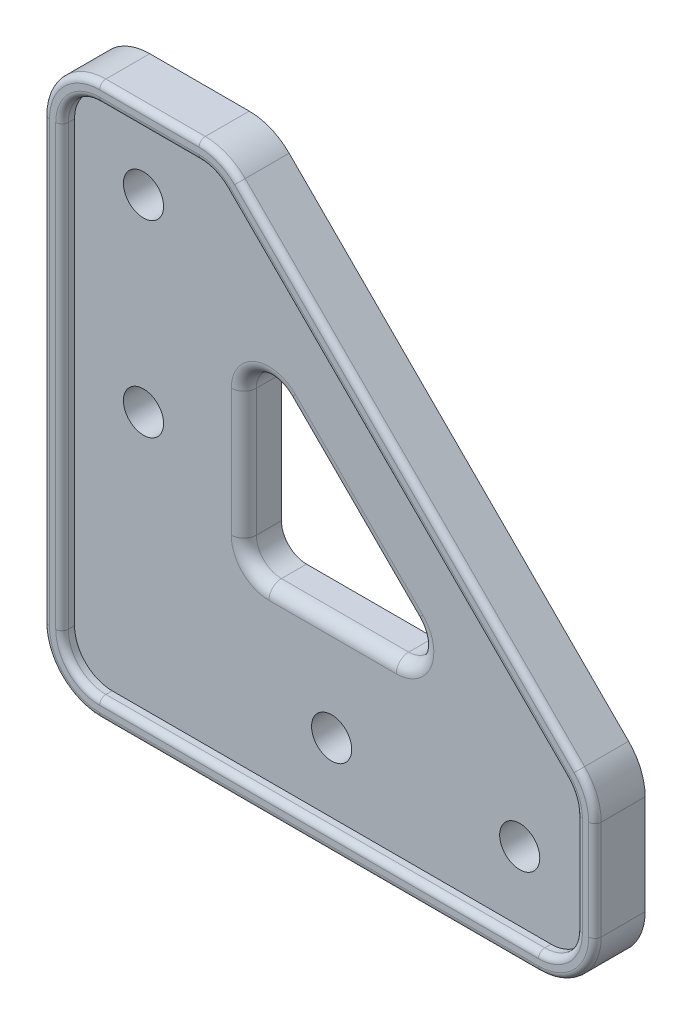
SolidWorks part; units mm, degrees
ref_plane "Front Plane" through (0, 0, 0) normal (0, 0, 1) x (1, 0, 0)
ref_plane "Top Plane" through (0, 0, 0) normal (0, 1, 0) x (1, 0, 0)
ref_plane "Right Plane" through (0, 0, 0) normal (1, 0, 0) x (0, 0, -1)
sketch "Sketch1" plane through (0, 0, 0) normal (0, 0, 1) x (1, 0, 0)
  line L0 (16.4645, 43.5355) -> (43.5355, 16.4645)
  line L1 (5, 0) -> (40, 0)
  line L2 (0, 5) -> (0, 40)
  line L3 (5, 45) -> (12.9289, 45)
  line L4 (45, 5) -> (45, 12.9289)
  arc A0 (0, 5) -> (5, 0) centre (5, 5) ccw
  arc A1 (45, 5) -> (40, 0) centre (40, 5) cw
  arc A2 (45, 12.9289) -> (43.5355, 16.4645) centre (40, 12.9289) ccw
  arc A3 (16.4645, 43.5355) -> (12.9289, 45) centre (12.9289, 40) ccw
  arc A4 (5, 45) -> (0, 40) centre (5, 40) ccw
  point P8 (0, 0)
  point P11 (45, 0)
  point P14 (45, 15)
  point P19 (0, 45)
  dimension "D4" = 5
  dimension "D1" = 45
  dimension "D2" = 45
  dimension "D3" = 15
extrude "Boss-Extrude1" add sketch "Sketch1" along normal blind 3
sketch "Sketch2" plane through (0, 0, 3) normal (0, 0, 1) x (1, 0, 0)
  line L0 (7.5, 7.5) -> (58.6399, 7.5) construction
  line L2 (55, 0) -> (-55, 0) construction
  line L4 (7.5, 40) -> (7.5, 5)
  line L5 (7.5, 40) -> (7.5, 7.5) construction
  circle A0 centre (7.5, 37.5) radius 1.6
  circle A2 centre (7.5, 22.5) radius 1.6
  circle A3 centre (22.5, 7.5) radius 1.6
  circle A4 centre (37.5, 7.5) radius 1.6
  dimension "D7" = 3.2
  dimension "D1" = 7.5
  dimension "D2" = 7.5
  dimension "D3" = 15
  dimension "D4" = 15
  dimension "D5" = 15
  dimension "D6" = 15
extrude "Cut-Extrude1" cut sketch "Sketch2" against normal through all
other "Move Face1" face at (1.9822, 1.9822, 1.5) face at (22.5, 0, 1.5) face at (43.0178, 1.9822, 1.5) face at (45, 8.9645, 1.5) face at (44.4436, 14.7695, 1.5) face at (30, 30, 1.5) face at (14.7695, 44.4436, 1.5) face at (8.9645, 45, 1.5) face at (1.9822, 43.0178, 1.5) face at (0, 22.5, 1.5) parameters "D1"=0.5
sketch "Sketch3" plane through (0, 0, 3) normal (0, 0, 1) x (1, 0, 0)
  line L5 (5, 2) -> (40, 2)
  line L6 (43, 5) -> (43, 12.9289)
  line L7 (42.1213, 15.0503) -> (15.0503, 42.1213)
  line L8 (12.9289, 43) -> (5, 43)
  line L9 (2, 40) -> (2, 5)
  line L10 (5, 0.5) -> (40, 0.5)
  line L11 (44.5, 5) -> (44.5, 12.9289)
  line L12 (43.182, 16.1109) -> (16.1109, 43.182)
  line L13 (12.9289, 44.5) -> (5, 44.5)
  line L14 (0.5, 40) -> (0.5, 5)
  line L15 (5, 0.5) -> (40, 0.5)
  line L16 (44.5, 5) -> (44.5, 12.9289)
  line L17 (43.182, 16.1109) -> (16.1109, 43.182)
  line L18 (12.9289, 44.5) -> (5, 44.5)
  line L19 (0.5, 40) -> (0.5, 5)
  arc A5 (40, 2) -> (43, 5) centre (40, 5) ccw
  arc A6 (43, 12.9289) -> (42.1213, 15.0503) centre (40, 12.9289) ccw
  arc A7 (15.0503, 42.1213) -> (12.9289, 43) centre (12.9289, 40) ccw
  arc A8 (5, 43) -> (2, 40) centre (5, 40) ccw
  arc A9 (2, 5) -> (5, 2) centre (5, 5) ccw
  arc A10 (0.5, 5) -> (5, 0.5) centre (5, 5) ccw
  arc A11 (40, 0.5) -> (44.5, 5) centre (40, 5) ccw
  arc A12 (44.5, 12.9289) -> (43.182, 16.1109) centre (40, 12.9289) ccw
  arc A13 (16.1109, 43.182) -> (12.9289, 44.5) centre (12.9289, 40) ccw
  arc A14 (5, 44.5) -> (0.5, 40) centre (5, 40) ccw
  arc A15 (0.5, 5) -> (5, 0.5) centre (5, 5) ccw
  arc A16 (40, 0.5) -> (44.5, 5) centre (40, 5) ccw
  arc A17 (44.5, 12.9289) -> (43.182, 16.1109) centre (40, 12.9289) ccw
  arc A18 (16.1109, 43.182) -> (12.9289, 44.5) centre (12.9289, 40) ccw
  arc A19 (5, 44.5) -> (0.5, 40) centre (5, 40) ccw
  dimension "D2" = 1.5
  dimension "D1" = 0
extrude "Boss-Extrude2" add sketch "Sketch3" along normal blind 1
fillet "Fillet1" radius 0.5 20 edges at (42.1213, 2.8787, 4) (43, 8.9645, 4) (42.7716, 14.077, 4) (28.5858, 28.5858, 4) (14.077, 42.7716, 4) (8.9645, 43, 4) (2.8787, 42.1213, 4) (2, 22.5, 4) (2.8787, 2.8787, 4) (22.5, 2, 4) (0.5, 22.5, 4) (1.818, 43.182, 4) (8.9645, 44.5, 4) (14.651, 44.1575, 4) (29.6464, 29.6464, 4) (44.1575, 14.651, 4) (44.5, 8.9645, 4) (43.182, 1.818, 4) (22.5, 0.5, 4) (1.818, 1.818, 4)
sketch "Sketch4" plane through (0, 0, 3) normal (0, 0, 1) x (1, 0, 0)
  line L0 (15.5, 27.6508) -> (15.5, 17.5)
  line L1 (17.5, 15.5) -> (27.6508, 15.5)
  line L2 (18.9142, 29.065) -> (29.065, 18.9142)
  line L3 (-702.1068, -702.1068) -> (34653.2323, 34653.2323) construction
  line L5 (40, 0.5) -> (5, 0.5) construction
  line L6 (16.1109, 43.182) -> (43.182, 16.1109) construction
  line L8 (0.5, 40) -> (0.5, 5) construction
  line L9 (16.1109, 43.182) -> (43.182, 16.1109) construction
  arc A0 (17.5, 15.5) -> (15.5, 17.5) centre (17.5, 17.5) cw
  arc A1 (18.9142, 29.065) -> (15.5, 27.6508) centre (17.5, 27.6508) ccw
  arc A2 (29.065, 18.9142) -> (27.6508, 15.5) centre (27.6508, 17.5) cw
  point P14 (15.5, 15.5)
  point P17 (15.5, 32.4792)
  point P20 (32.4792, 15.5)
  dimension "D5" = 2
  dimension "D6" = 2
  dimension "D7" = 2
  dimension "D1" = 8
  dimension "D2" = 15
  dimension "D3" = 15
  dimension "D4" = 8
extrude "Cut-Extrude2" cut sketch "Sketch4" against normal through all
fillet "Fillet2" radius 1 6 edges at (16.0858, 16.0858, 3) (22.5754, 15.5, 3) (29.4985, 16.7346, 3) (23.9896, 23.9896, 3) (16.7346, 29.4985, 3) (15.5, 22.5754, 3)
